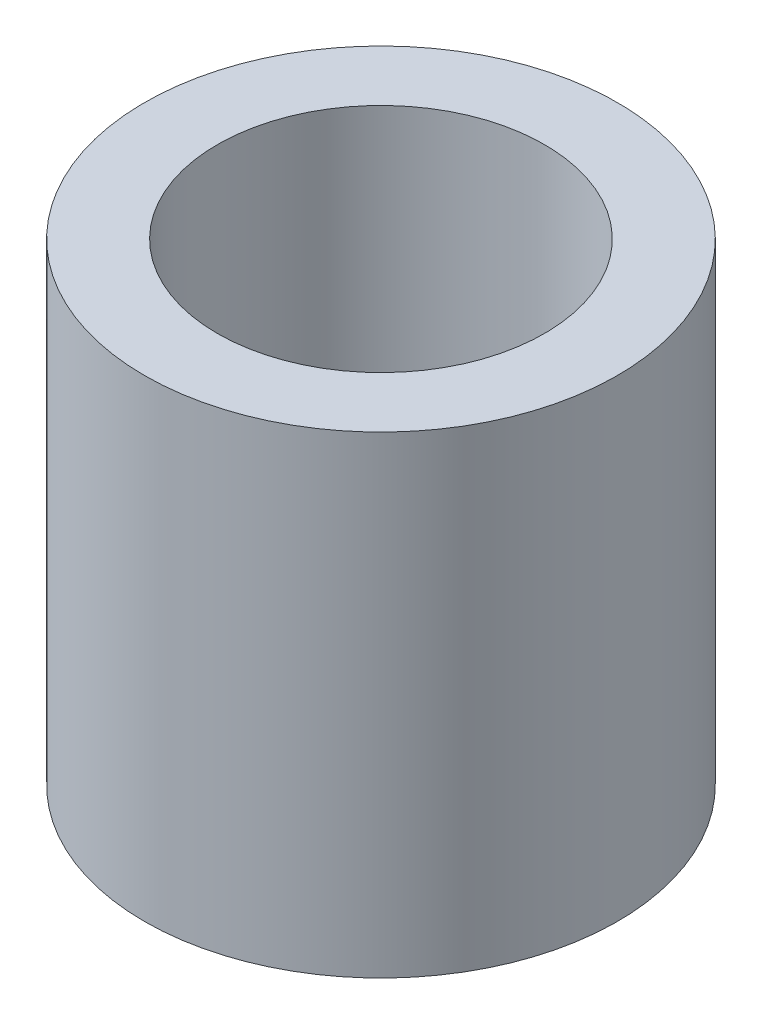
SolidWorks part; units mm, degrees
ref_plane "Front Plane" through (0, 0, 0) normal (0, 0, 1) x (1, 0, 0)
ref_plane "Top Plane" through (0, 0, 0) normal (0, 1, 0) x (1, 0, 0)
ref_plane "Right Plane" through (0, 0, 0) normal (1, 0, 0) x (0, 0, -1)
sketch "Sketch1" plane through (0, 0, 0) normal (0, 1, 0) x (1, 0, 0)
  circle A0 centre (0, 0) radius 25
  circle A1 centre (0, 0) radius 17.3
  dimension "D1" = 50
  dimension "D2" = 34.6
extrude "Boss-Extrude1" add sketch "Sketch1" along normal blind 50
